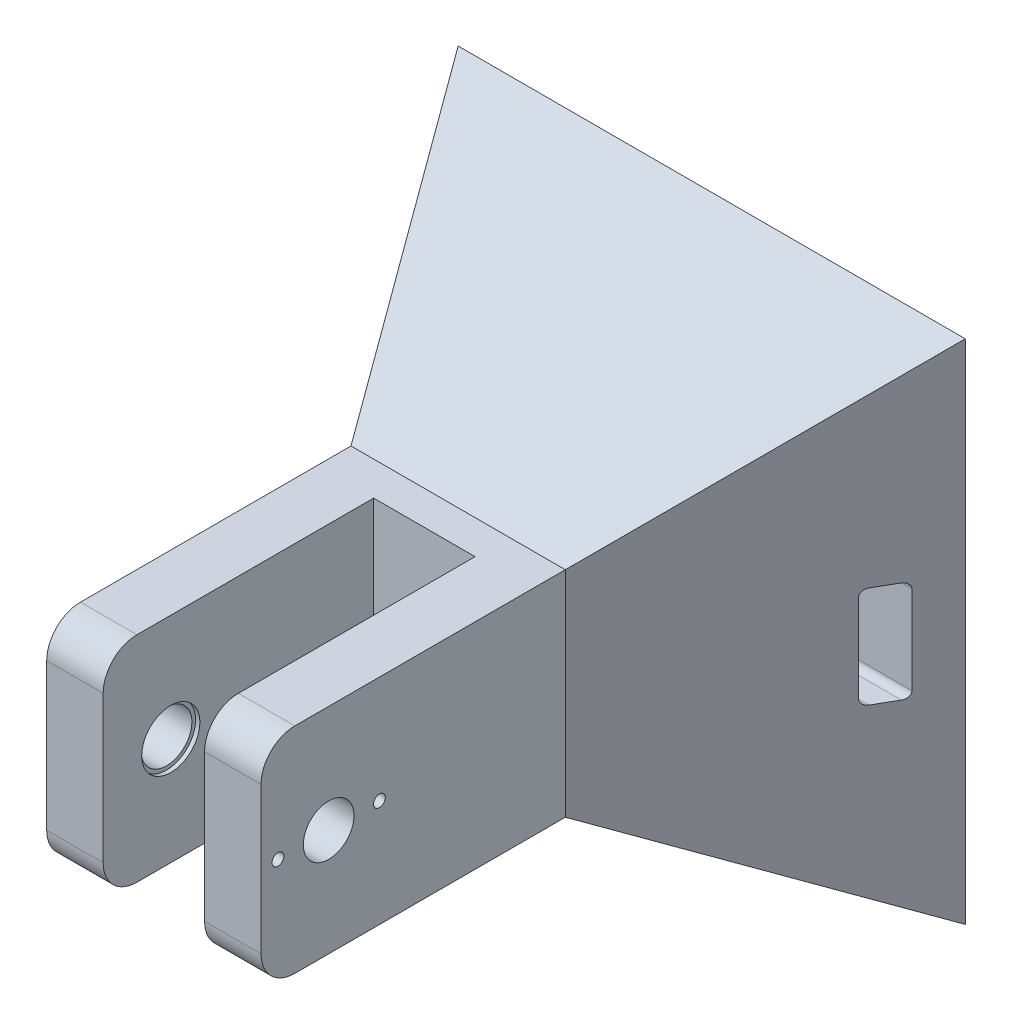
SolidWorks part; units mm, degrees
ref_plane "Front Plane" through (0, 0, 0) normal (0, 0, 1) x (1, 0, 0)
ref_plane "Top Plane" through (0, 0, 0) normal (0, 1, 0) x (1, 0, 0)
ref_plane "Right Plane" through (0, 0, 0) normal (1, 0, 0) x (0, 0, -1)
sketch "Sketch2" plane through (0, 0, 0) normal (0, 0, 1) x (1, 0, 0)
  line L1 (0, 0) -> (150, 0)
  line L2 (0, 0) -> (0, 150)
  line L3 (0, 150) -> (150, 150)
  line L4 (150, 0) -> (150, 150)
  dimension "D1" = 150
  dimension "D2" = 150
extrude "Boss-Extrude1" add sketch "Sketch2" along normal blind 75 draft 30
sketch "Sketch3" plane through (0, 0, 75) normal (0, 0, 1) x (1, 0, 0)
  line L4 (43.3013, 106.6987) -> (43.3013, 43.3013)
  line L5 (43.3013, 43.3013) -> (106.6987, 43.3013)
  line L6 (106.6987, 43.3013) -> (106.6987, 106.6987)
  line L7 (106.6987, 106.6987) -> (43.3013, 106.6987)
  line L8 (43.3013, 106.6987) -> (43.3013, 43.3013)
  line L9 (43.3013, 43.3013) -> (106.6987, 43.3013)
  line L10 (106.6987, 43.3013) -> (106.6987, 106.6987)
  line L11 (106.6987, 106.6987) -> (43.3013, 106.6987)
  dimension "D1" = 0
extrude "Boss-Extrude2" add sketch "Sketch3" along normal blind 90
sketch "Sketch4" plane through (0, 0, 165) normal (0, 0, 1) x (1, 0, 0)
  line L0 (106.6987, 106.6987) -> (43.3013, 106.6987) construction
  line L1 (60, 106.6987) -> (90, 106.6987)
  line L2 (60, 106.6987) -> (60, 43.3013)
  line L3 (60, 43.3013) -> (90, 43.3013)
  line L4 (90, 106.6987) -> (90, 43.3013)
  line L5 (43.3013, 43.3013) -> (106.6987, 43.3013) construction
  point P8 (75, 106.6987)
  point P9 (75, 106.6987)
  dimension "D1" = 30
extrude "Cut-Extrude1" cut sketch "Sketch4" against normal blind 80
fillet "Fillet1" radius 10 4 edges at (51.6506, 43.3013, 165) (98.3494, 43.3013, 165) (98.3494, 106.6987, 165) (51.6506, 106.6987, 165)
sketch "Sketch5" plane through (43.3013, 0, 0) normal (-1, 0, 0) x (0, 0, 1)
  line L0 (165, 96.6987) -> (165, 53.3013) construction
  circle A0 centre (145, 75) radius 7.5
  point P4 (165, 75)
  dimension "D2" = 15
  dimension "D1" = 20
extrude "Cut-Extrude2" cut sketch "Sketch5" against normal up to surface (63.3975 mm away) up to face at (106.6987, 75, 132.357)
sketch "Sketch6" plane through (0, 0, 0) normal (0, 0, -1) x (-1, 0, 0)
  line L0 (-150, 0) -> (-150, 150) construction
  line L1 (-25, 125) -> (-125, 125)
  line L2 (-25, 125) -> (-25, 25)
  line L3 (-25, 25) -> (-125, 25)
  line L4 (-125, 125) -> (-125, 25)
  line L5 (-150, 150) -> (0, 150) construction
  point P4 (-125, 75)
  point P7 (-150, 75)
  point P8 (-75, 125)
  point P11 (-75, 150)
  dimension "D1" = 100
extrude "Cut-Extrude3" cut sketch "Sketch6" against normal blind 20
sketch "Sketch7" plane through (125, 0, 0) normal (-1, 0, 0) x (0, 0, 1)
  line L0 (20, 125) -> (20, 25) construction
  line L1 (20, 90) -> (10, 90)
  line L2 (20, 90) -> (20, 60)
  line L3 (20, 60) -> (10, 60)
  line L4 (10, 90) -> (10, 60)
  line L5 (0, 125) -> (0, 25) construction
  point P8 (10, 75)
  point P9 (0, 75)
  dimension "D1" = 30
  dimension "D2" = 10
extrude "Cut-Extrude4" cut sketch "Sketch7" against normal through all
fillet "Fillet2" radius 2 4 edges at (134.6132, 60, 10) (134.6132, 90, 10) (131.7265, 90, 20) (131.7265, 60, 20)
sketch "Sketch8" plane through (106.6987, 0, 0) normal (1, 0, 0) x (0, 0, -1)
  arc A0 (-127.9, 75) -> (-132.1, 75) centre (-130, 75) ccw construction
  circle A1 centre (-130, 75) radius 2.1 construction
  arc A2 (-157.9, 75) -> (-162.1, 75) centre (-160, 75) ccw construction
  circle A3 centre (-160, 75) radius 2.1 construction
  circle A4 centre (-160, 75) radius 1.75
  circle A5 centre (-130, 75) radius 1.75
  dimension "D1" = 3.5
extrude "Cut-Extrude5" cut sketch "Sketch8" against normal up to surface (16.6987 mm away) up to face at (90, 82.5, 145)
sketch "Sketch9" plane through (90, 0, 0) normal (-1, 0, 0) x (0, 0, 1)
  circle A4 centre (160, 75) radius 3.25
  circle A5 centre (130, 75) radius 3.25
  circle A7 centre (130, 75) radius 1.75 construction
  circle A8 centre (160, 75) radius 1.75 construction
  circle A9 centre (130, 75) radius 1.75
  circle A10 centre (160, 75) radius 1.75
  dimension "D1" = 6.5
extrude "Cut-Extrude6" cut sketch "Sketch9" against normal blind 3
sketch "Sketch10" plane through (60, 0, 0) normal (1, 0, 0) x (0, 0, -1)
  circle A2 centre (-145, 75) radius 8.6
  circle A3 centre (-145, 75) radius 8.6
  dimension "D1" = 1.1
extrude "Cut-Extrude7" cut sketch "Sketch10" against normal blind 1.25
ref_plane "Plane1" through (75, 0, 0) normal (1, 0, 0) x (0, 0, -1)
mirror "Mirror1" about plane through (75, 0, 0) normal (1, 0, 0) of "Cut-Extrude7"
